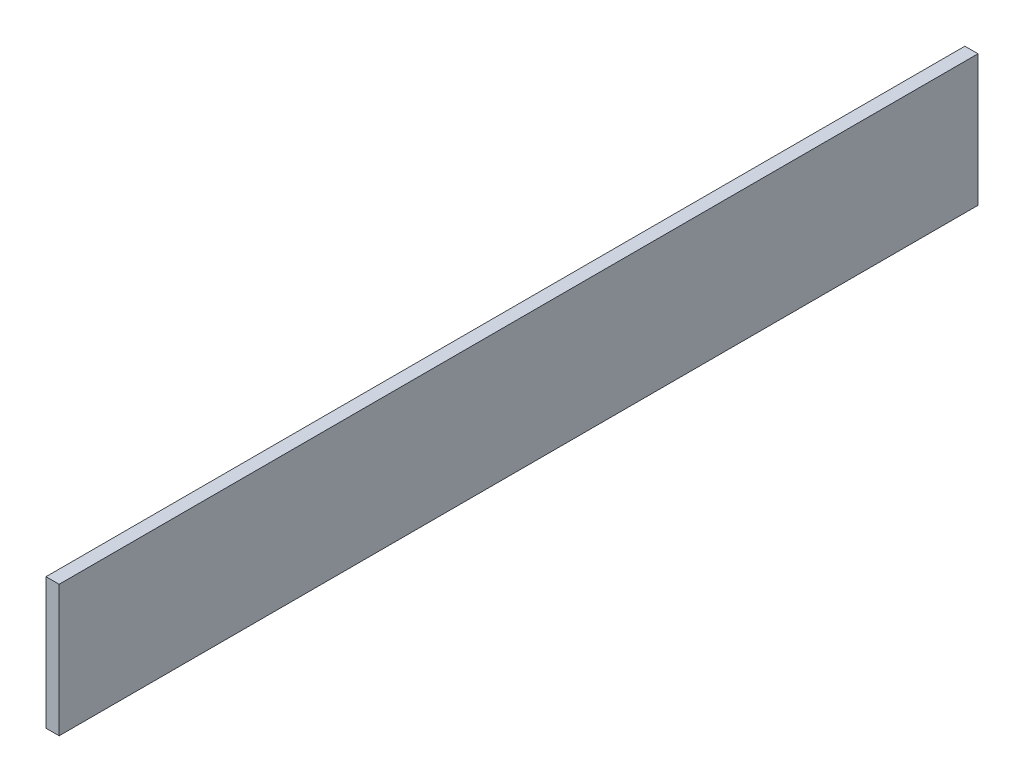
SolidWorks part; units mm, degrees
ref_plane "Front Plane" through (0, 0, 0) normal (0, 0, 1) x (1, 0, 0)
ref_plane "Top Plane" through (0, 0, 0) normal (0, 1, 0) x (1, 0, 0)
ref_plane "Right Plane" through (0, 0, 0) normal (1, 0, 0) x (0, 0, -1)
sketch "Sketch1" plane through (0, 0, 0) normal (0, 1, 0) x (1, 0, 0)
  line L1 (0, 0) -> (1, 0)
  line L2 (0, 0) -> (0, 70)
  line L3 (0, 70) -> (1, 70)
  line L4 (1, 0) -> (1, 70)
  dimension "D1" = 1
  dimension "D2" = 70
extrude "Boss-Extrude1" add sketch "Sketch1" along normal blind 10
